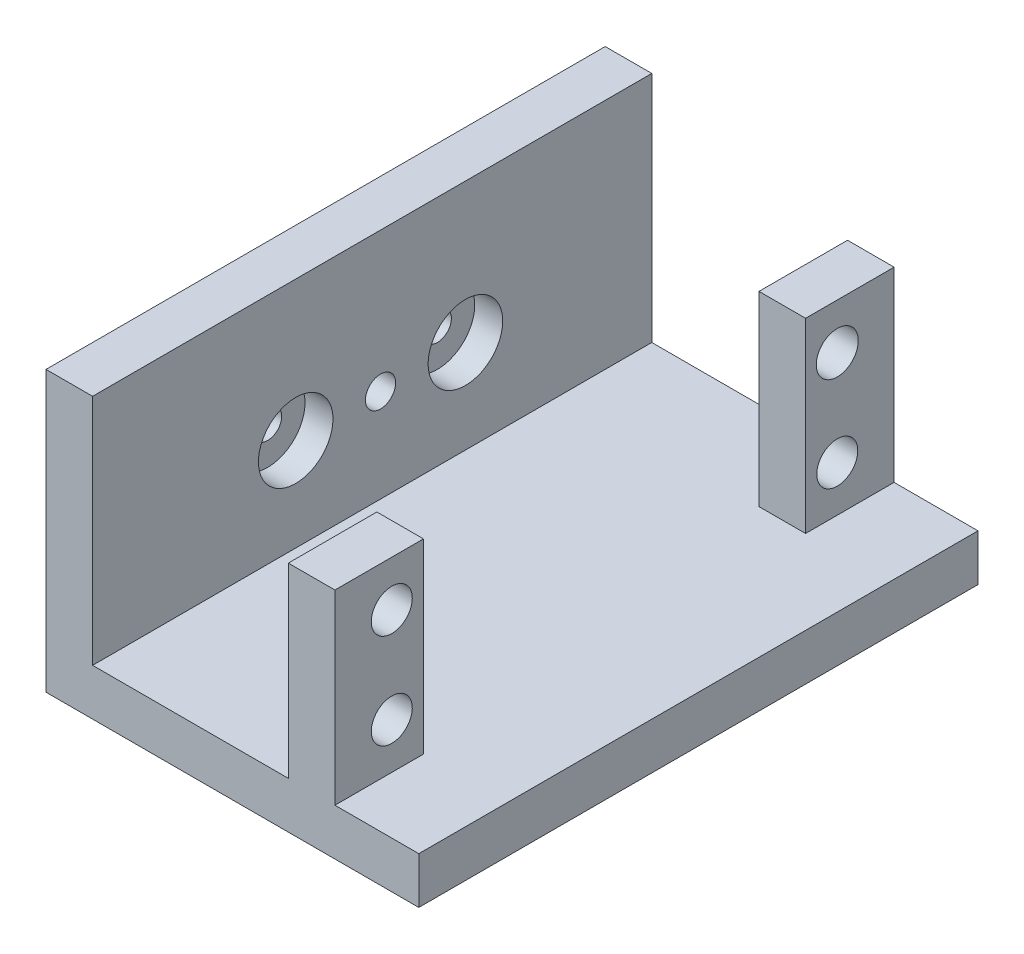
SolidWorks part; units mm, degrees
ref_plane "Alzado" through (0, 0, 0) normal (0, 0, 1) x (1, 0, 0)
ref_plane "Planta" through (0, 0, 0) normal (0, 1, 0) x (1, 0, 0)
ref_plane "Vista lateral" through (0, 0, 0) normal (1, 0, 0) x (0, 0, -1)
sketch "Croquis1" plane through (0, 0, 0) normal (0, 0, 1) x (1, 0, 0)
  line L0 (0, 0) -> (40, 0)
  line L1 (40, 0) -> (40, 5)
  line L2 (40, 5) -> (31, 5)
  line L3 (5, 5) -> (5, 30)
  line L4 (5, 30) -> (0, 30)
  line L5 (0, 30) -> (0, 0)
  line L6 (26, 5) -> (26, 25)
  line L7 (26, 25) -> (31, 25)
  line L8 (31, 25) -> (31, 5)
  line L9 (26, 5) -> (5, 5)
  dimension "D1" = 5
  dimension "D2" = 30
  dimension "D3" = 5
  dimension "D4" = 40
  dimension "D5" = 5
  dimension "D6" = 26
  dimension "D7" = 20
extrude "Saliente-Extruir1" add sketch "Croquis1" along normal blind 60
sketch "Croquis2" plane through (0, 25, 0) normal (0, 1, 0) x (1, 0, 0)
  line L1 (31, -50.5) -> (26, -50.5)
  line L2 (31, -50.5) -> (31, -9.5)
  line L3 (31, -9.5) -> (26, -9.5)
  line L4 (26, -50.5) -> (26, -9.5)
  line L8 (40, -60) -> (40, 0) construction
  line L9 (26, -60) -> (26, 0) construction
  line L11 (26, -9.5) -> (26, 0) construction
  line L12 (26, -60) -> (26, -50.5) construction
  dimension "D1" = 41
  dimension "D2" = 9
extrude "Cortar-Extruir1" cut sketch "Croquis2" against normal up to surface (20 mm away) up to face at (15.5, 5, 30)
sketch "Croquis7" plane through (31, 0, 0) normal (1, 0, 0) x (0, 0, -1)
  circle A0 centre (-53.9, 20.1) radius 2.2
  circle A1 centre (-53.9, 9.9) radius 2.2
  circle A2 centre (-6.1, 9.9) radius 2.2
  circle A3 centre (-6.1, 20.1) radius 2.2535
extrude "Cortar-Extruir5" cut sketch "Croquis7" against normal blind 10
sketch "Croquis8" plane through (0, 0, 0) normal (-1, 0, 0) x (0, 0, 1)
  circle A0 centre (20, 15) radius 1.5
  circle A1 centre (38.209, 15) radius 1.5
  dimension "D1" = 3
extrude "Cortar-Extruir6" cut sketch "Croquis8" against normal blind 10
sketch "Croquis9" plane through (5, 0, 0) normal (1, 0, 0) x (0, 0, -1)
  line L0 (-38.209, 15) -> (-20, 15) construction
  circle A0 centre (-20, 15) radius 4
  circle A1 centre (-29.1045, 15) radius 1.6213
  circle A2 centre (-38.209, 15) radius 4
  dimension "D1" = 8
  dimension "D2" = 8
extrude "Cortar-Extruir7" cut sketch "Croquis9" against normal blind 3
sketch "Croquis10" plane through (2, 0, 0) normal (1, 0, 0) x (0, 0, -1)
  circle A1 centre (-29.1045, 15) radius 1.6213
  circle A2 centre (-29.1045, 15) radius 1.6213
  dimension "D1" = 0
extrude "Cortar-Extruir8" cut sketch "Croquis10" against normal blind 10
